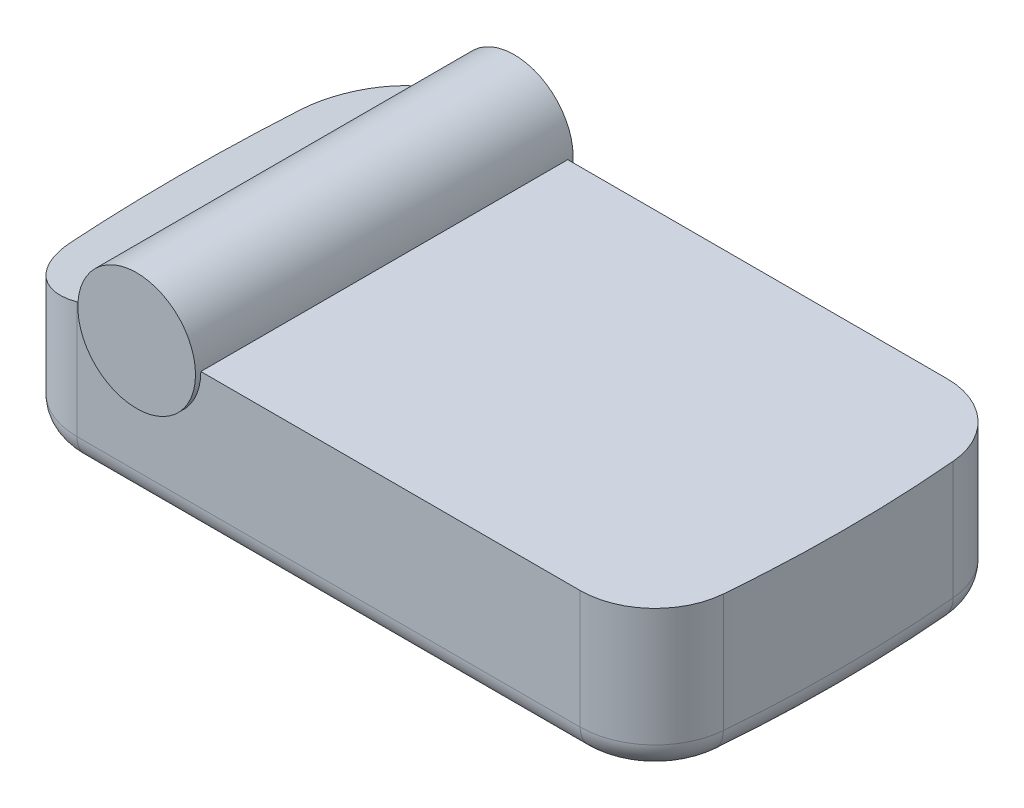
SolidWorks part; units mm, degrees
ref_plane "Front Plane" through (0, 0, 0) normal (0, 0, 1) x (1, 0, 0)
ref_plane "Top Plane" through (0, 0, 0) normal (0, 1, 0) x (1, 0, 0)
ref_plane "Right Plane" through (0, 0, 0) normal (1, 0, 0) x (0, 0, -1)
sketch "Sketch1" plane through (0, 0, 0) normal (0, 1, 0) x (1, 0, 0)
  line L0 (-29.7867, 17.15) -> (-29.7867, -17.15) construction
  line L1 (-23.52, 17.15) -> (23.52, 17.15)
  line L3 (-23.52, -17.15) -> (23.52, -17.15)
  line L5 (-29.7867, 17.15) -> (29.7867, -17.15) construction
  line L6 (-29.7867, -17.15) -> (29.7867, 17.15) construction
  line L7 (29.7867, 17.15) -> (29.7867, -17.15) construction
  arc A0 (-30.4949, 10.7421) -> (-30.4949, -10.7421) centre (96.05, 0) ccw
  arc A1 (30.4949, 10.7421) -> (30.4949, -10.7421) centre (-96.05, 0) cw
  arc A2 (23.52, 17.15) -> (30.4949, 10.7421) centre (23.52, 10.15) cw
  arc A3 (23.52, -17.15) -> (30.4949, -10.7421) centre (23.52, -10.15) ccw
  arc A4 (-30.4949, -10.7421) -> (-23.52, -17.15) centre (-23.52, -10.15) ccw
  arc A5 (-23.52, 17.15) -> (-30.4949, 10.7421) centre (-23.52, 10.15) ccw
  point P0 (0, 0)
  point P8 (-30.95, 0)
  point P9 (30.95, 0)
  point P10 (-29.7867, 17.15)
  dimension "D3" = 127
  dimension "D1" = 7
  dimension "D2" = 34.3
  dimension "D4" = 61.9
extrude "Boss-Extrude1" add sketch "Sketch1" along normal blind 13.6
fillet "Fillet1" radius 2.54 8 edges at (0, 0, 17.15) (0, 0, -17.15) (30.95, 0, 0) (-30.95, 0, 0) (-28.2558, 0, -15.3048) (28.2558, 0, -15.3048) (28.2558, 0, 15.3048) (-28.2558, 0, 15.3048)
sketch "Sketch3" plane through (0, 0, 17.15) normal (0, 0, 1) x (1, 0, 0)
  line L2 (-29.7867, 13.6) -> (-29.7867, 2.54) construction
  line L4 (-23.52, 13.6) -> (23.52, 13.6) construction
  circle A0 centre (-17.439, 13.6) radius 5.5
  dimension "D1" = 11
  dimension "D2" = 12.3477
extrude "Boss-Extrude2" add sketch "Sketch3" along normal blind 0.5 and the other way offset from surface (34.8 mm away) 0.5 other way up to face at (0, 8.07, -17.15)
ref_plane "Plane1" through (30.95, 0, 0) normal (1, 0, 0) x (0, 0, -1)
sketch "Sketch5" plane through (0, 0, 17.15) normal (0, 0, 1) x (1, 0, 0)
  line L0 (-22.939, 13.6) -> (-30.95, 11.4535)
  line L3 (-30.95, 13.6) -> (-22.939, 13.6)
  line L4 (-30.95, 13.6) -> (-30.95, 2.54) construction
  line L5 (-30.95, 11.4535) -> (-30.95, 13.6)
  dimension "D1" = 15
extrude "Cut-Extrude2" cut sketch "Sketch5" against normal through all
